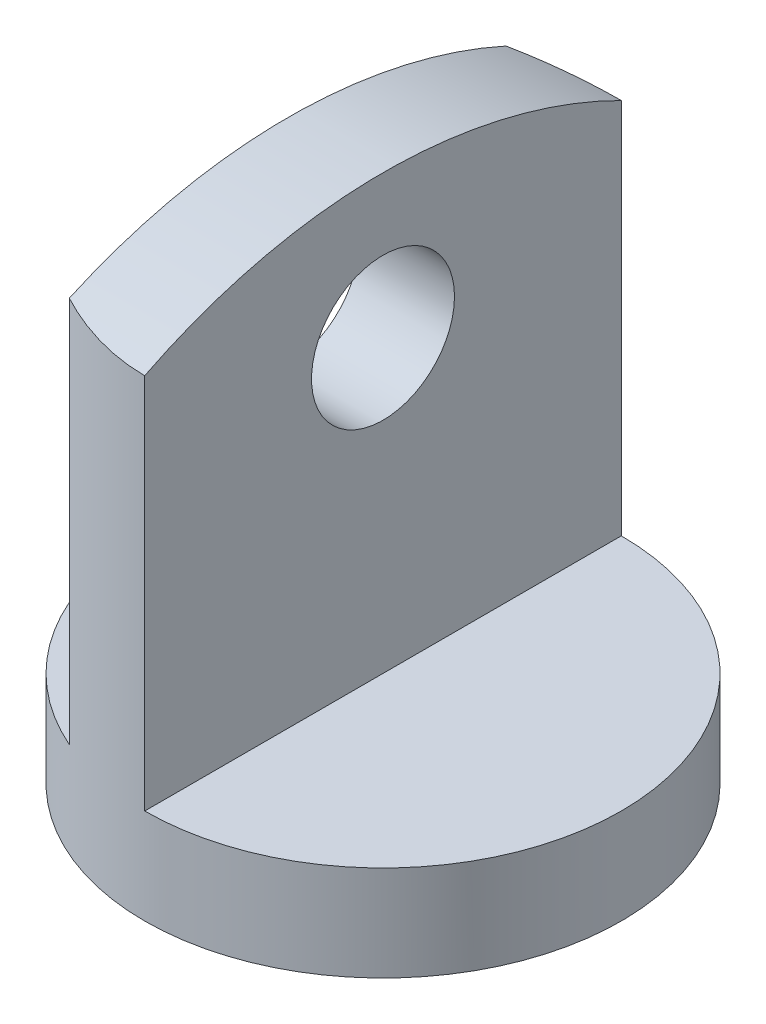
SolidWorks part; units mm, degrees
ref_plane "Front Plane" through (0, 0, 0) normal (0, 0, 1) x (1, 0, 0)
ref_plane "Top Plane" through (0, 0, 0) normal (0, 1, 0) x (1, 0, 0)
ref_plane "Right Plane" through (0, 0, 0) normal (1, 0, 0) x (0, 0, -1)
sketch "Sketch1" plane through (0, 0, 0) normal (0, 0, 1) x (1, 0, 0)
  line L0 (0, 188.75) -> (0, -158.75) construction
  line L1 (0, 50) -> (125, 50)
  line L2 (125, 50) -> (125, 0)
  line L3 (125, 0) -> (250, 0)
  line L4 (250, 0) -> (250, 100)
  line L5 (250, 100) -> (0, 100)
  line L6 (0, 50) -> (0, 100)
  dimension "D1" = 250
  dimension "D2" = 250
  dimension "D3" = 100
  dimension "D4" = 50
revolve "Revolve1" add sketch "Sketch1" angle 360 about L0
sketch "Sketch3" plane through (0, 100, 0) normal (0, 1, 0) x (1, 0, 0)
  line L0 (0, 250) -> (0, -250)
  line L1 (-100, 229.1288) -> (-100, -229.1288)
  circle A0 centre (0, 0) radius 250 construction
  arc A1 (-100, 229.1288) -> (0, 250) centre (0, 0) cw
  arc A2 (-100, -229.1288) -> (0, -250) centre (0, 0) ccw
  dimension "D1" = 100
extrude "Boss-Extrude1" add sketch "Sketch3" along normal blind 455
sketch "Sketch4" plane through (0, 0, 0) normal (1, 0, 0) x (0, 0, -1)
  line L0 (-250, 555) -> (250, 555) construction
  line L1 (-250, 0) -> (250, 0) construction
  line L2 (-250, 555) -> (-250, 100) construction
  line L3 (250, 555) -> (250, 100) construction
  line L4 (-250, 495.5048) -> (-250, 555)
  line L5 (-250, 555) -> (250, 555)
  line L6 (250, 555) -> (250, 495.5048)
  circle A0 centre (0, 405) radius 75
  arc A1 (-250, 495.5048) -> (250, 495.5048) centre (0, 0) cw
  line M3 (250, 100) -> (250, 555)
  line M4 (250, 555) -> (-250, 555)
  line M5 (-250, 555) -> (-250, 100)
  dimension "D1" = 150
  dimension "D2" = 150
extrude "Cut-Extrude1" cut sketch "Sketch4" against normal up to surface (100 mm away) contours A0 | A1 L5 M5 | A1 M4 M3 up to face at (-100, 327.5, 0)
